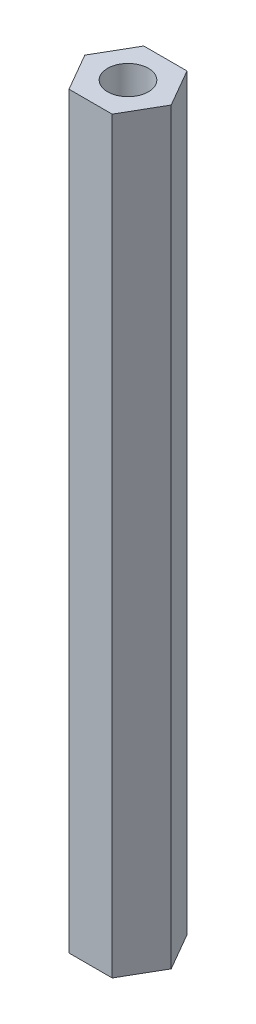
SolidWorks part; units mm, degrees
ref_plane "Front Plane" through (0, 0, 0) normal (0, 0, 1) x (1, 0, 0)
ref_plane "Top Plane" through (0, 0, 0) normal (0, 1, 0) x (1, 0, 0)
ref_plane "Right Plane" through (0, 0, 0) normal (1, 0, 0) x (0, 0, -1)
sketch "Sketch1" plane through (0, 0, 0) normal (0, 1, 0) x (1, 0, 0)
  line L1 (3.1754, 0) -> (1.5877, 2.75)
  line L2 (1.5877, 2.75) -> (-1.5877, 2.75)
  line L3 (-1.5877, 2.75) -> (-3.1754, 0)
  line L4 (-3.1754, 0) -> (-1.5877, -2.75)
  line L5 (-1.5877, -2.75) -> (1.5877, -2.75)
  line L6 (1.5877, -2.75) -> (3.1754, 0)
  circle A0 centre (0, 0) radius 2.75 construction
  dimension "D1" = 5.5
extrude "Boss-Extrude1" add sketch "Sketch1" along normal blind 55
sketch "Sketch2" plane through (0, 55, 0) normal (0, 1, 0) x (1, 0, 0)
  circle A0 centre (0, 0) radius 1.5
  dimension "D1" = 3
extrude "Cut-Extrude1" cut sketch "Sketch2" against normal blind 10
ref_plane "Plane1" through (0, 27.5, 0) normal (0, -1, 0) x (-1, 0, 0)
mirror "Mirror1" about plane through (0, 27.5, 0) normal (0, -1, 0) of "Cut-Extrude1"
